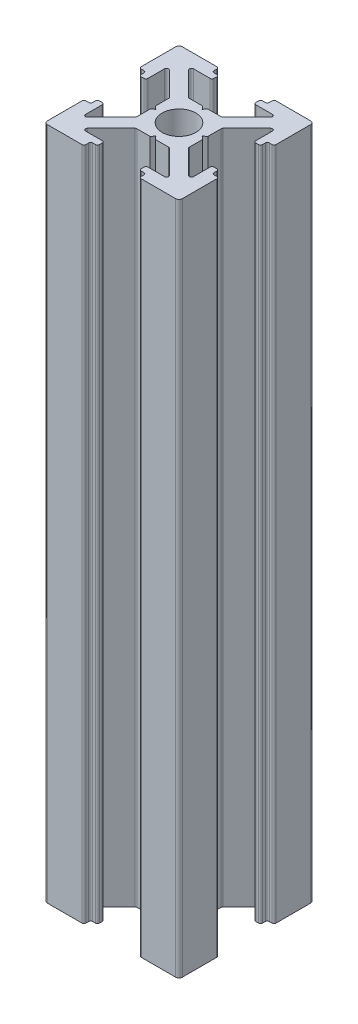
SolidWorks part; units mm, degrees
material "1060 Alloy"
ref_plane "Front Plane" through (0, 0, 0) normal (0, 0, 1) x (1, 0, 0)
ref_plane "Top Plane" through (0, 0, 0) normal (0, 1, 0) x (1, 0, 0)
ref_plane "Right Plane" through (0, 0, 0) normal (1, 0, 0) x (0, 0, -1)
sketch "Sketch1" plane through (0, 0, 0) normal (1, 0, 0) x (0, 0, -1)
  line L0 (0, 0) -> (0, 100)
  dimension "D1" = 100
other "Vuong NHOMDH20X20(1)"
ref_plane "Plane1" through (0, 0, 0) normal (0, 1, 0) x (0, 0, 1)
sketch "Sketch2" plane through (0, 0, 0) normal (0, 1, 0) x (0, 0, 1)
  line L0 (0, 10) -> (0, 0) construction
  line L1 (0, 0) -> (10, 0) construction
  line L2 (0.3857, 3.9) -> (2.3607, 3.9)
  line L3 (2.5729, 3.9879) -> (6.0729, 7.4879)
  line L4 (5.8607, 8) -> (3.4, 8)
  line L5 (3.1, 8.3) -> (3.1, 8.7)
  line L6 (3.4, 9) -> (3.8, 9)
  line L7 (4.1, 9.3) -> (4.1, 9.7)
  line L8 (4.4, 10) -> (9.5, 10)
  line L9 (10, 9.5) -> (10, 4.4)
  line L10 (9.7, 4.1) -> (9.3, 4.1)
  line L11 (9, 3.8) -> (9, 3.4)
  line L12 (8.7, 3.1) -> (8.3, 3.1)
  line L13 (8, 3.4) -> (8, 5.8607)
  line L14 (7.4879, 6.0729) -> (3.9879, 2.5729)
  line L15 (3.9, 2.3607) -> (3.9, 0.3857)
  line L16 (10, 10) -> (0, 0) construction
  line L17 (3.9, -0.3857) -> (3.9, -2.3607)
  line L18 (3.9879, -2.5729) -> (7.4879, -6.0729)
  line L19 (8, -5.8607) -> (8, -3.4)
  line L20 (8.3, -3.1) -> (8.7, -3.1)
  line L21 (9, -3.4) -> (9, -3.8)
  line L22 (9.3, -4.1) -> (9.7, -4.1)
  line L23 (10, -4.4) -> (10, -9.5)
  line L24 (9.5, -10) -> (4.4, -10)
  line L25 (4.1, -9.7) -> (4.1, -9.3)
  line L26 (3.8, -9) -> (3.4, -9)
  line L27 (3.1, -8.7) -> (3.1, -8.3)
  line L28 (3.4, -8) -> (5.8607, -8)
  line L29 (6.0729, -7.4879) -> (2.5729, -3.9879)
  line L30 (2.3607, -3.9) -> (0.3857, -3.9)
  line L31 (10, -10) -> (0, 0) construction
  line L32 (-0.3857, -3.9) -> (-2.3607, -3.9)
  line L33 (-2.5729, -3.9879) -> (-6.0729, -7.4879)
  line L34 (-5.8607, -8) -> (-3.4, -8)
  line L35 (-3.1, -8.3) -> (-3.1, -8.7)
  line L36 (-3.4, -9) -> (-3.8, -9)
  line L37 (-4.1, -9.3) -> (-4.1, -9.7)
  line L38 (-4.4, -10) -> (-9.5, -10)
  line L39 (-10, -9.5) -> (-10, -4.4)
  line L40 (-9.7, -4.1) -> (-9.3, -4.1)
  line L41 (-9, -3.8) -> (-9, -3.4)
  line L42 (-8.7, -3.1) -> (-8.3, -3.1)
  line L43 (-8, -3.4) -> (-8, -5.8607)
  line L44 (-7.4879, -6.0729) -> (-3.9879, -2.5729)
  line L45 (-3.9, -2.3607) -> (-3.9, -0.3857)
  line L46 (-10, -10) -> (0, 0) construction
  line L47 (-3.9, 0.3857) -> (-3.9, 2.3607)
  line L48 (-3.9879, 2.5729) -> (-7.4879, 6.0729)
  line L49 (-8, 5.8607) -> (-8, 3.4)
  line L50 (-8.3, 3.1) -> (-8.7, 3.1)
  line L51 (-9, 3.4) -> (-9, 3.8)
  line L52 (-9.3, 4.1) -> (-9.7, 4.1)
  line L53 (-10, 4.4) -> (-10, 9.5)
  line L54 (-9.5, 10) -> (-4.4, 10)
  line L55 (-4.1, 9.7) -> (-4.1, 9.3)
  line L56 (-3.8, 9) -> (-3.4, 9)
  line L57 (-3.1, 8.7) -> (-3.1, 8.3)
  line L58 (-3.4, 8) -> (-5.8607, 8)
  line L59 (-6.0729, 7.4879) -> (-2.5729, 3.9879)
  line L60 (-2.3607, 3.9) -> (-0.3857, 3.9)
  line L61 (-10, 10) -> (0, 0) construction
  line L62 (-0.3857, 3.9) -> (0, 3.4404)
  line L63 (0, 3.4404) -> (0.3857, 3.9)
  line L64 (3.4404, 0) -> (3.9, -0.3857)
  line L65 (3.9, 0.3857) -> (3.4404, 0)
  line L66 (0, -3.4404) -> (-0.3857, -3.9)
  line L67 (0.3857, -3.9) -> (0, -3.4404)
  line L68 (-3.4404, 0) -> (-3.9, 0.3857)
  line L69 (-3.9, -0.3857) -> (-3.4404, 0)
  arc A0 (4.1, 9.7) -> (4.4, 10) centre (4.4, 9.7) cw
  arc A1 (3.8, 9) -> (4.1, 9.3) centre (3.8, 9.3) ccw
  arc A2 (3.1, 8.7) -> (3.4, 9) centre (3.4, 8.7) cw
  arc A3 (3.4, 8) -> (3.1, 8.3) centre (3.4, 8.3) cw
  arc A4 (10, 4.4) -> (9.7, 4.1) centre (9.7, 4.4) cw
  arc A5 (9.3, 4.1) -> (9, 3.8) centre (9.3, 3.8) ccw
  arc A6 (9, 3.4) -> (8.7, 3.1) centre (8.7, 3.4) cw
  arc A7 (8.3, 3.1) -> (8, 3.4) centre (8.3, 3.4) cw
  arc A8 (3.9879, 2.5729) -> (3.9, 2.3607) centre (4.2, 2.3607) ccw
  arc A9 (2.3607, 3.9) -> (2.5729, 3.9879) centre (2.3607, 4.2) ccw
  arc A10 (8, 5.8607) -> (7.4879, 6.0729) centre (7.7, 5.8607) ccw
  arc A11 (6.0729, 7.4879) -> (5.8607, 8) centre (5.8607, 7.7) ccw
  arc A12 (9.5, 10) -> (10, 9.5) centre (9.5, 9.5) cw
  arc A13 (9.7, -4.1) -> (10, -4.4) centre (9.7, -4.4) cw
  arc A14 (9, -3.8) -> (9.3, -4.1) centre (9.3, -3.8) ccw
  arc A15 (8.7, -3.1) -> (9, -3.4) centre (8.7, -3.4) cw
  arc A16 (8, -3.4) -> (8.3, -3.1) centre (8.3, -3.4) cw
  arc A17 (4.4, -10) -> (4.1, -9.7) centre (4.4, -9.7) cw
  arc A18 (4.1, -9.3) -> (3.8, -9) centre (3.8, -9.3) ccw
  arc A19 (3.4, -9) -> (3.1, -8.7) centre (3.4, -8.7) cw
  arc A20 (3.1, -8.3) -> (3.4, -8) centre (3.4, -8.3) cw
  arc A21 (2.5729, -3.9879) -> (2.3607, -3.9) centre (2.3607, -4.2) ccw
  arc A22 (3.9, -2.3607) -> (3.9879, -2.5729) centre (4.2, -2.3607) ccw
  arc A23 (5.8607, -8) -> (6.0729, -7.4879) centre (5.8607, -7.7) ccw
  arc A24 (7.4879, -6.0729) -> (8, -5.8607) centre (7.7, -5.8607) ccw
  arc A25 (10, -9.5) -> (9.5, -10) centre (9.5, -9.5) cw
  arc A26 (-4.1, -9.7) -> (-4.4, -10) centre (-4.4, -9.7) cw
  arc A27 (-3.8, -9) -> (-4.1, -9.3) centre (-3.8, -9.3) ccw
  arc A28 (-3.1, -8.7) -> (-3.4, -9) centre (-3.4, -8.7) cw
  arc A29 (-3.4, -8) -> (-3.1, -8.3) centre (-3.4, -8.3) cw
  arc A30 (-10, -4.4) -> (-9.7, -4.1) centre (-9.7, -4.4) cw
  arc A31 (-9.3, -4.1) -> (-9, -3.8) centre (-9.3, -3.8) ccw
  arc A32 (-9, -3.4) -> (-8.7, -3.1) centre (-8.7, -3.4) cw
  arc A33 (-8.3, -3.1) -> (-8, -3.4) centre (-8.3, -3.4) cw
  arc A34 (-3.9879, -2.5729) -> (-3.9, -2.3607) centre (-4.2, -2.3607) ccw
  arc A35 (-2.3607, -3.9) -> (-2.5729, -3.9879) centre (-2.3607, -4.2) ccw
  arc A36 (-8, -5.8607) -> (-7.4879, -6.0729) centre (-7.7, -5.8607) ccw
  arc A37 (-6.0729, -7.4879) -> (-5.8607, -8) centre (-5.8607, -7.7) ccw
  arc A38 (-9.5, -10) -> (-10, -9.5) centre (-9.5, -9.5) cw
  arc A39 (-9.7, 4.1) -> (-10, 4.4) centre (-9.7, 4.4) cw
  arc A40 (-9, 3.8) -> (-9.3, 4.1) centre (-9.3, 3.8) ccw
  arc A41 (-8.7, 3.1) -> (-9, 3.4) centre (-8.7, 3.4) cw
  arc A42 (-8, 3.4) -> (-8.3, 3.1) centre (-8.3, 3.4) cw
  arc A43 (-4.4, 10) -> (-4.1, 9.7) centre (-4.4, 9.7) cw
  arc A44 (-4.1, 9.3) -> (-3.8, 9) centre (-3.8, 9.3) ccw
  arc A45 (-3.4, 9) -> (-3.1, 8.7) centre (-3.4, 8.7) cw
  arc A46 (-3.1, 8.3) -> (-3.4, 8) centre (-3.4, 8.3) cw
  arc A47 (-2.5729, 3.9879) -> (-2.3607, 3.9) centre (-2.3607, 4.2) ccw
  arc A48 (-3.9, 2.3607) -> (-3.9879, 2.5729) centre (-4.2, 2.3607) ccw
  arc A49 (-5.8607, 8) -> (-6.0729, 7.4879) centre (-5.8607, 7.7) ccw
  arc A50 (-7.4879, 6.0729) -> (-8, 5.8607) centre (-7.7, 5.8607) ccw
  arc A51 (-10, 9.5) -> (-9.5, 10) centre (-9.5, 9.5) cw
  circle A52 centre (0, 0) radius 2.5
  point P3 (0, 0)
  point P23 (4.1, 10)
  point P26 (4.1, 9)
  point P33 (10, 4.1)
  point P46 (8, 6.585)
  point P179 (0, 0)
  point P188 (0, 0)
  dimension "D8" = 0.3
  dimension "D9" = 0.5
  dimension "D11" = 5
  dimension "D1" = 10
  dimension "D2" = 8.2
  dimension "D3" = 6.2
  dimension "D4" = 2
  dimension "D5" = 1
  dimension "D6" = 13.17
  dimension "D7" = 7.8
  dimension "D12" = 0.6
  dimension "D13" = 80
  dimension "D10" = 4
  dimension "D14" = 4
